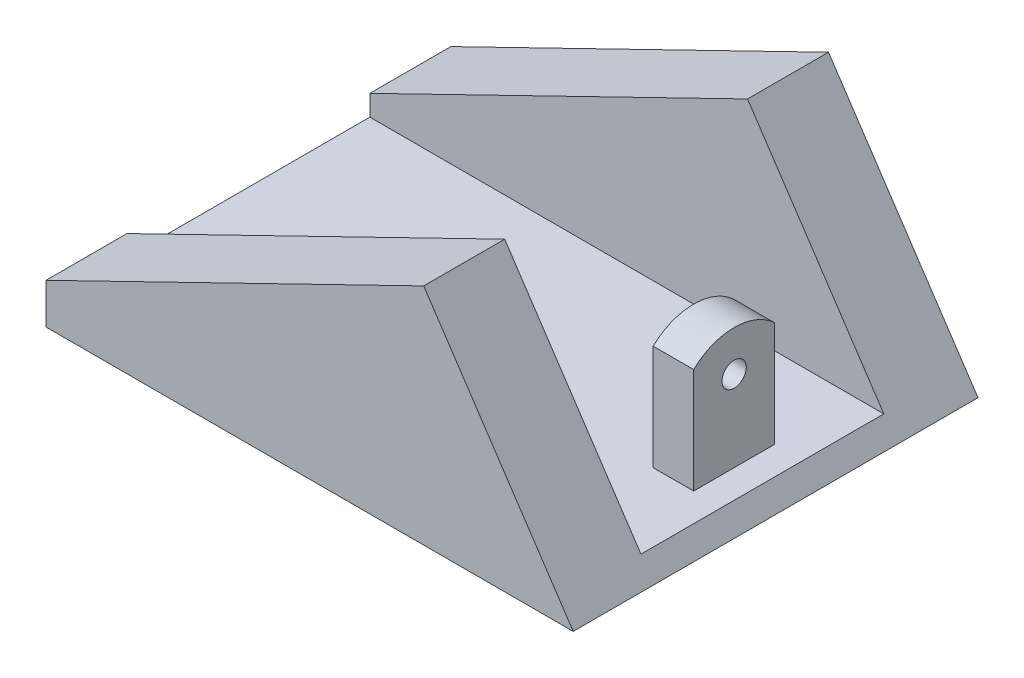
SolidWorks part; units mm, degrees
ref_plane "Front Plane" through (0, 0, 0) normal (0, 0, 1) x (1, 0, 0)
ref_plane "Top Plane" through (0, 0, 0) normal (0, 1, 0) x (1, 0, 0)
ref_plane "Right Plane" through (0, 0, 0) normal (1, 0, 0) x (0, 0, -1)
sketch "Sketch1" plane through (0, 0, 0) normal (0, 0, 1) x (1, 0, 0)
  line L0 (0, 0) -> (0, 27.725)
  line L1 (0, 27.725) -> (65.122, 27.725)
  line L2 (65.122, 27.725) -> (65.122, 0)
  line L3 (65.122, 0) -> (0, 0)
  dimension "D1" = 65.122
  dimension "D2" = 27.725
extrude "Boss-Extrude1" add sketch "Sketch1" along normal blind 50
sketch "Sketch3" plane through (0, 27.725, 0) normal (0, 1, 0) x (1, 0, 0)
  line L0 (0, -10) -> (65.122, -10)
  line L1 (0, -50) -> (0, 0) construction
  line L2 (65.122, -50) -> (65.122, 0) construction
  line L3 (65.122, -10) -> (65.122, -40)
  line L4 (65.122, -40) -> (0, -40)
  line L5 (0, -40) -> (0, -10)
  line L6 (65.122, 0) -> (0, 0) construction
  line L7 (65.122, -50) -> (0, -50) construction
  dimension "D1" = 10
  dimension "D2" = 10
extrude "Cut-Extrude1" cut sketch "Sketch3" against normal blind 25.272
sketch "Sketch4" plane through (0, 0, 50) normal (0, 0, 1) x (1, 0, 0)
  line L0 (0, 5) -> (46.655, 27.725)
  line L1 (0, 27.725) -> (0, 0) construction
  line L2 (65.122, 27.725) -> (0, 27.725) construction
  line L3 (46.655, 27.725) -> (65.122, 0)
  line L4 (46.655, 27.725) -> (65.122, 27.725)
  line L5 (65.122, 27.725) -> (65.122, 0)
  line L6 (46.655, 27.725) -> (0, 27.725)
  line L7 (0, 27.725) -> (0, 5)
  line L8 (0, 5) -> (0, 27.725)
  line L9 (46.655, 27.725) -> (0, 5)
  line L10 (0, 27.725) -> (46.655, 27.725)
  line M3 (65.122, 27.725) -> (0, 27.725)
  line M4 (0, 27.725) -> (0, 0)
  dimension "D1" = 5
  dimension "D2" = 46.655
extrude "Cut-Extrude2" cut sketch "Sketch4" against normal through all contours L0 M4 M3
sketch "Sketch5" plane through (0, 0, 50) normal (0, 0, 1) x (1, 0, 0)
  line L0 (46.655, 27.725) -> (65.122, 0)
  line L1 (65.122, 0) -> (65.122, 27.725)
  line L2 (65.122, 27.725) -> (46.655, 27.725)
extrude "Cut-Extrude3" cut sketch "Sketch5" against normal through all
sketch "Sketch6" plane through (0, 2.453, 0) normal (0, 1, 0) x (1, 0, 0)
  line L0 (55, -20) -> (55, -30)
  line L1 (55, -30) -> (60, -30)
  line L2 (60, -30) -> (60, -20)
  line L3 (60, -20) -> (55, -20)
  line L4 (0, -10) -> (0, -40) construction
  line L5 (63.4881, -10) -> (0, -10) construction
  dimension "D1" = 5
  dimension "D2" = 55
  dimension "D3" = 10
  dimension "D4" = 10
extrude "Boss-Extrude2" add sketch "Sketch6" along normal blind 15
sketch "Sketch7" plane through (60, 0, 0) normal (1, 0, 0) x (0, 0, -1)
  line L1 (-30, 17.453) -> (-30, 2.453) construction
  line L4 (-20, 17.453) -> (-20, 2.453) construction
  line L5 (-30, 15.453) -> (-30, 17.453)
  line L6 (-20, 15.453) -> (-20, 17.453)
  line L7 (-30, 17.453) -> (-24.889, 17.831)
  line L8 (-24.889, 17.831) -> (-20, 17.453)
  arc A1 (-30, 15.453) -> (-20, 15.453) centre (-25, 10.203) cw
extrude "Cut-Extrude5" cut sketch "Sketch7" against normal blind 15
sketch "Sketch9" plane through (60, 0, 0) normal (1, 0, 0) x (0, 0, -1)
  line L0 (-30, 2.453) -> (-20, 2.453) construction
  line L1 (-20, 15.453) -> (-20, 2.453) construction
  circle A0 centre (-25, 12.453) radius 1.5
  dimension "D2" = 3
  dimension "D1" = 10
  dimension "D3" = 5
extrude "Cut-Extrude6" cut sketch "Sketch9" against normal through all
sketch "Sketch10" plane through (0, 2.453, 0) normal (0, 1, 0) x (1, 0, 0)
  line L0 (0, -40) -> (63.4881, -40) construction
  circle A0 centre (46.1061, -35) radius 1.575
  circle A1 centre (46.1061, -13) radius 1.575
  dimension "D1" = 3.15
  dimension "D2" = 3.15
  dimension "D3" = 22
  dimension "D4" = 5
extrude "Cut-Extrude7" cut sketch "Sketch10" against normal through all
